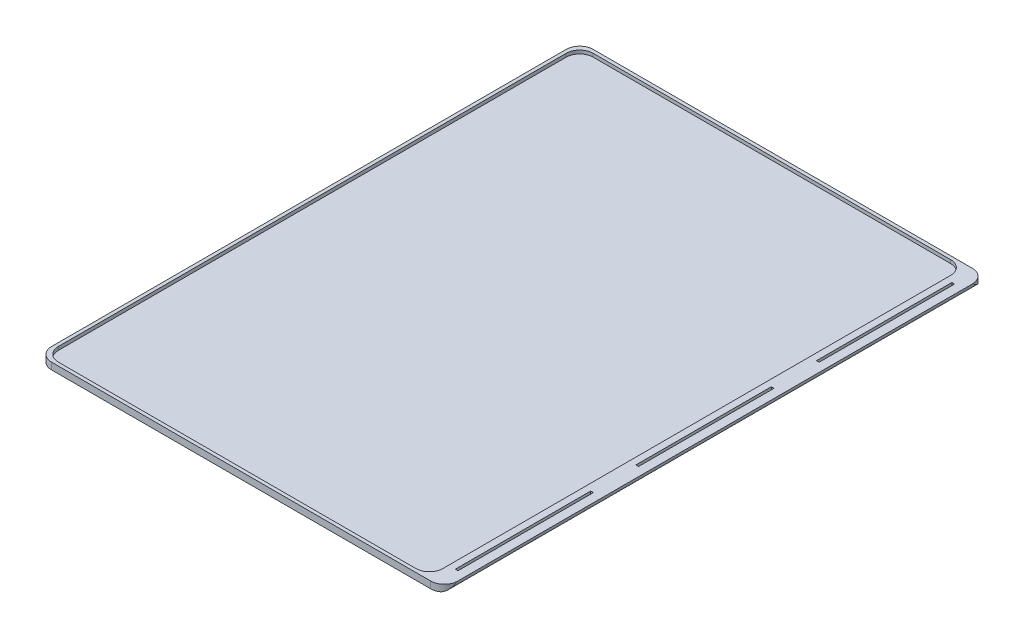
SolidWorks part; units mm, degrees
material "7075-O (SS)"
ref_plane "Front Plane" through (0, 0, 0) normal (0, 0, 1) x (1, 0, 0)
ref_plane "Top Plane" through (0, 0, 0) normal (0, 1, 0) x (1, 0, 0)
ref_plane "Right Plane" through (0, 0, 0) normal (1, 0, 0) x (0, 0, -1)
sketch "Sketch1" plane through (0, 0, 0) normal (0, 1, 0) x (1, 0, 0)
  line L1 (-150, -200) -> (150, -200)
  line L2 (-150, -200) -> (-150, 200)
  line L3 (-150, 200) -> (150, 200)
  line L4 (150, -200) -> (150, 200)
  line L5 (-150, -200) -> (150, 200) construction
  line L6 (-150, 200) -> (150, -200) construction
  point P0 (0, 0)
  dimension "D1" = 400
  dimension "D2" = 300
extrude "Boss-Extrude1" add sketch "Sketch1" along normal blind 5
sketch "Sketch6" plane through (0, 0, 200) normal (0, 0, 1) x (1, 0, 0)
  line L0 (-150, 5) -> (150, 5) construction
  line L1 (-150, 0) -> (150, 0) construction
  line L2 (145, 0) -> (150, 0)
  line L3 (150, 0) -> (150, 5)
  arc A0 (150, 5) -> (145, 0) centre (145, 5) cw
extrude "Cut-Extrude2" cut sketch "Sketch6" against normal up to surface (400 mm away) up to face at (0, 2.5, -200)
sketch "Sketch7" plane through (0, 5, 0) normal (0, 1, 0) x (1, 0, 0)
  line L0 (142.5, 200.926) -> (142.5, -49799.074) construction
  line L1 (0, 0) -> (50000, 0) construction
  line L2 (143.5, -183.3333) -> (141.5, -83.3333) construction
  line L4 (145, -200) -> (145, 200)
  line L5 (-150, -200) -> (145, -200)
  line L6 (-150, 200) -> (-150, -200)
  line L7 (145, 200) -> (-150, 200)
  line L8 (145, -200) -> (145, 200) construction
  line L13 (141.5, -50) -> (143.5, -50)
  line L14 (141.5, -50) -> (141.5, 50)
  line L15 (141.5, 50) -> (143.5, 50)
  line L16 (143.5, -50) -> (143.5, 50)
  line L17 (141.5, -50) -> (143.5, 50) construction
  line L18 (141.5, 50) -> (143.5, -50) construction
  line L19 (143.5, 83.3333) -> (141.5, 83.3333)
  line L20 (143.5, 83.3333) -> (143.5, 183.3333)
  line L21 (143.5, 183.3333) -> (141.5, 183.3333)
  line L22 (141.5, 83.3333) -> (141.5, 183.3333)
  line L23 (143.5, 83.3333) -> (141.5, 183.3333) construction
  line L24 (143.5, 183.3333) -> (141.5, 83.3333) construction
  line L25 (143.5, -83.3333) -> (141.5, -183.3333) construction
  line L26 (141.5, -83.3333) -> (141.5, -183.3333)
  line L27 (143.5, -183.3333) -> (141.5, -183.3333)
  line L28 (143.5, -83.3333) -> (143.5, -183.3333)
  line L29 (143.5, -83.3333) -> (141.5, -83.3333)
  point P9 (142.5, 0)
  point P16 (142.5, 133.3333)
  point P23 (142.5, -133.3333)
  dimension "D2" = 2.5
  dimension "D3" = 100
  dimension "D4" = 2
  dimension "D5" = 133.3333
extrude "Cut-Extrude3" cut sketch "Sketch7" against normal through all both and the other way through all
sketch "Sketch8" plane through (0, 5, 0) normal (0, 1, 0) x (1, 0, 0)
  line L0 (141.5, -50) -> (141.5, 50) construction
  line L1 (145, 200) -> (-150, 200) construction
  line L2 (-150, 200) -> (-150, -200) construction
  line L3 (-150, -200) -> (145, -200) construction
  line L4 (141.5, -50) -> (141.5, 50) construction
  line L5 (145, 200) -> (-150, 200) construction
  line L6 (-150, 200) -> (-150, -200) construction
  line L7 (-150, -200) -> (145, -200) construction
  line L9 (-147.5, -197.5) -> (136.5, -197.5)
  line L10 (-147.5, -197.5) -> (-147.5, 197.5)
  line L11 (-147.5, 197.5) -> (136.5, 197.5)
  line L12 (136.5, -197.5) -> (136.5, 197.5)
  line L13 (-147.5, -197.5) -> (136.5, 197.5) construction
  line L14 (-147.5, 197.5) -> (136.5, -197.5) construction
  point P4 (-5.5, 0)
  point P11 (0, 0)
  dimension "D1" = 5
  dimension "D2" = 5
  dimension "D3" = 5
extrude "Cut-Extrude4" cut sketch "Sketch8" against normal blind 2.5
fillet "Fillet1" radius 10 6 edges at (-147.5, 3.75, -197.5) (-150, 2.5, -200) (136.5, 3.75, -197.5) (136.5, 3.75, 197.5) (-147.5, 3.75, 197.5) (-150, 2.5, 200)
sketch "Sketch9" plane through (0, 5, 0) normal (0, 1, 0) x (1, 0, 0)
  line L0 (150, 200) -> (-140, 200) construction
  line L1 (150, -200) -> (150, 200) construction
  line L2 (140, 200) -> (150, 200)
  line L3 (150, 200) -> (150, 190)
  line L4 (0, 0) -> (50000, 0) construction
  line L5 (150, -200) -> (150, -190)
  line L6 (140, -200) -> (150, -200)
  arc A0 (140, 200) -> (150, 190) centre (140, 190) cw
  arc A1 (140, -200) -> (150, -190) centre (140, -190) ccw
  dimension "D1" = 10
extrude "Cut-Extrude5" cut sketch "Sketch9" against normal through all both and the other way through all
equation "\"thiccness\" = 5mm"
equation "\"width\"= 400mm"
equation "\"length\"= 300mm"
equation "\"wall_width\"= 5mm"
equation "\"wall_depth\"= 2.5mm"
equation "\"D1@Sketch1\"=\"width\""
equation "\"D2@Sketch1\"=\"length\""
equation "\"D1@Boss-Extrude1\"=\"thiccness\""
equation "\"hinge_width\"= 100mm"
equation "\"hinge_length\"= 2mm"
equation "\"D2@Sketch7\"=\"wall_width\"/2"
equation "\"D3@Sketch7\"=\"hinge_width\""
equation "\"D4@Sketch7\"=\"hinge_length\""
equation "\"D5@Sketch7\"=\"width\"/3"
equation "\"D1@Sketch8\"=\"wall_width\""
equation "\"D2@Sketch8\"=\"wall_width\""
equation "\"D3@Sketch8\"=\"wall_width\""
equation "\"D1@Cut-Extrude4\"=\"wall_depth\""
equation "\"fillet_radius\"= 10mm"
equation "\"D1@Fillet1\"=\"fillet_radius\""
equation "\"D1@Sketch9\"=\"fillet_radius\""
